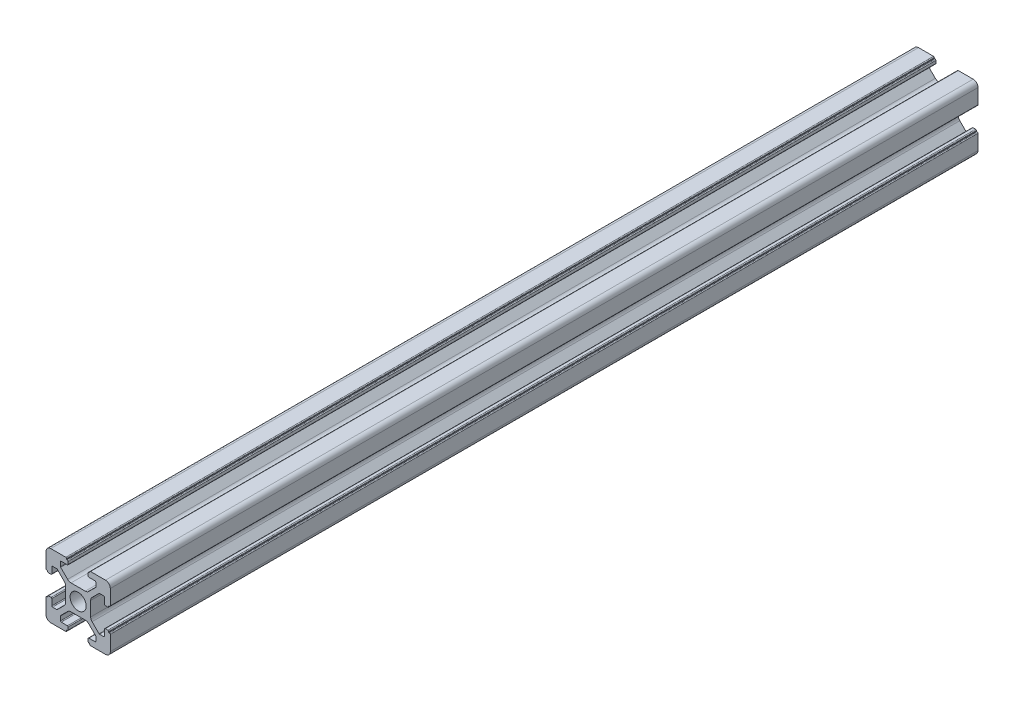
SolidWorks part; units mm, degrees
ref_plane "前视基准面" through (0, 0, 0) normal (0, 0, 1) x (1, 0, 0)
ref_plane "上视基准面" through (0, 0, 0) normal (0, 1, 0) x (1, 0, 0)
ref_plane "右视基准面" through (0, 0, 0) normal (1, 0, 0) x (0, 0, -1)
sketch "草图1" plane through (0, 0, 0) normal (0, 0, 1) x (1, 0, 0)
  line L0 (0, 0) -> (0, 5.5) construction
  line L1 (-8.5023, -10.0023) -> (-3.85, -10.0023)
  line L2 (-10.0023, -8.5023) -> (-10.0023, -3.85)
  line L3 (-8.5023, 10.0023) -> (-3.85, 10.0023)
  line L4 (10.0023, -8.5023) -> (10.0023, -3.85)
  line L5 (-10.0023, -10.0023) -> (10.0023, 10.0023) construction
  line L6 (-10.0023, 10.0023) -> (10.0023, -10.0023) construction
  line L7 (-2.218, -3.9) -> (2.218, -3.9)
  line L8 (-3.9, -2.218) -> (-3.9, 2.218)
  line L9 (-2.218, 3.9) -> (2.218, 3.9)
  line L10 (3.9, -2.218) -> (3.9, 2.218)
  line L11 (-3.9, -3.9) -> (3.9, 3.9) construction
  line L12 (-3.9, 3.9) -> (3.9, -3.9) construction
  line L13 (-5.25, -8.2) -> (-3.35, -8.2)
  line L14 (-8.2, -5.25) -> (-8.2, -3.35)
  line L15 (-5.25, 8.2) -> (-3.35, 8.2)
  line L16 (8.2, -5.25) -> (8.2, -3.35)
  line L17 (-8.2, -8.2) -> (8.2, 8.2) construction
  line L18 (-8.2, 8.2) -> (8.2, -8.2) construction
  line L19 (-7.95, 5.5) -> (-6.6642, 5.5)
  line L20 (0, 0) -> (5.5, 0) construction
  line L23 (-5.5, 7.95) -> (-5.5, 6.6642)
  line L26 (0, 0) -> (-0.5303, 0.5303)
  line L27 (3.2787, 4.3393) -> (5.4268, 6.4874)
  line L28 (0, 0) -> (0.5303, -0.5303)
  line L29 (5.5, 6.6642) -> (5.5, 7.95)
  line L30 (4.3393, 3.2787) -> (6.4874, 5.4268)
  line L31 (6.6642, 5.5) -> (7.95, 5.5)
  line L32 (4.3393, -3.2787) -> (6.4874, -5.4268)
  line L33 (3.2787, -4.3393) -> (5.4268, -6.4874)
  line L34 (-3.2787, -4.3393) -> (-5.4268, -6.4874)
  line L35 (-4.3393, -3.2787) -> (-6.4874, -5.4268)
  line L36 (-4.3393, 3.2787) -> (-6.4874, 5.4268)
  line L37 (-3.2787, 4.3393) -> (-5.4268, 6.4874)
  line L38 (3.1, -8.45) -> (3.1, -9.2523)
  line L39 (8.45, 3.1) -> (9.2523, 3.1)
  line L40 (-5.5, -6.6642) -> (-5.5, -7.95)
  line L41 (-6.6642, -5.5) -> (-7.95, -5.5)
  line L42 (5.5, -6.6642) -> (5.5, -7.95)
  line L43 (6.6642, -5.5) -> (7.95, -5.5)
  line L44 (9.2523, -3.1) -> (8.45, -3.1)
  line L46 (10.0023, 3.85) -> (10.0023, 8.5023)
  line L47 (8.2, 3.35) -> (8.2, 5.25)
  line L48 (-3.1, -9.2523) -> (-3.1, -8.45)
  line L49 (-8.45, -3.1) -> (-9.2523, -3.1)
  line L50 (-9.2523, 3.1) -> (-8.45, 3.1)
  line L51 (-3.1, 8.45) -> (-3.1, 9.2523)
  line L52 (3.1, 9.2523) -> (3.1, 8.45)
  line L53 (3.85, 10.0023) -> (8.5023, 10.0023)
  line L54 (3.35, 8.2) -> (5.25, 8.2)
  line L55 (-10.0023, 3.85) -> (-10.0023, 8.5023)
  line L56 (-8.2, 3.35) -> (-8.2, 5.25)
  line L57 (3.35, -8.2) -> (5.25, -8.2)
  line L58 (3.85, -10.0023) -> (8.5023, -10.0023)
  line L59 (9.7523, -3.6) -> (9.5023, -3.6)
  line L61 (9.7523, 3.6) -> (9.5023, 3.6)
  line L62 (9.5023, -3.6) -> (9.5023, -3.35)
  line L63 (3.6, -9.7523) -> (3.6, -9.5023)
  line L64 (3.35, -9.5023) -> (3.6, -9.5023)
  line L65 (9.5023, 3.35) -> (9.5023, 3.6)
  line L66 (-3.6, -9.5023) -> (-3.35, -9.5023)
  line L67 (-3.6, -9.7523) -> (-3.6, -9.5023)
  line L68 (-9.7523, -3.6) -> (-9.5023, -3.6)
  line L69 (-9.5023, -3.35) -> (-9.5023, -3.6)
  line L70 (-9.5023, 3.6) -> (-9.5023, 3.35)
  line L71 (-9.7523, 3.6) -> (-9.5023, 3.6)
  line L72 (-3.6, 9.7523) -> (-3.6, 9.5023)
  line L73 (-3.35, 9.5023) -> (-3.6, 9.5023)
  line L74 (3.6, 9.5023) -> (3.35, 9.5023)
  line L75 (3.6, 9.7523) -> (3.6, 9.5023)
  circle A0 centre (0, 0) radius 2.5
  arc A1 (10.0023, 8.5023) -> (8.5023, 10.0023) centre (8.5023, 8.5023) ccw
  arc A2 (8.5023, -10.0023) -> (10.0023, -8.5023) centre (8.5023, -8.5023) ccw
  arc A3 (-10.0023, -8.5023) -> (-8.5023, -10.0023) centre (-8.5023, -8.5023) ccw
  arc A4 (-10.0023, 8.5023) -> (-8.5023, 10.0023) centre (-8.5023, 8.5023) cw
  arc A5 (-9.5023, -3.35) -> (-9.2523, -3.1) centre (-9.2523, -3.35) cw
  arc A6 (-9.7523, -3.6) -> (-10.0023, -3.85) centre (-9.7523, -3.85) ccw
  arc A7 (-8.45, -3.1) -> (-8.2, -3.35) centre (-8.45, -3.35) cw
  arc A8 (-7.95, -5.5) -> (-8.2, -5.25) centre (-7.95, -5.25) cw
  arc A9 (-6.4874, -5.4268) -> (-6.6642, -5.5) centre (-6.6642, -5.25) cw
  arc A10 (-5.4268, -6.4874) -> (-5.5, -6.6642) centre (-5.25, -6.6642) ccw
  arc A11 (-5.5, -7.95) -> (-5.25, -8.2) centre (-5.25, -7.95) ccw
  arc A12 (-3.6, -9.7523) -> (-3.85, -10.0023) centre (-3.85, -9.7523) cw
  arc A13 (-3.35, -9.5023) -> (-3.1, -9.2523) centre (-3.35, -9.2523) ccw
  arc A14 (-3.1, -8.45) -> (-3.35, -8.2) centre (-3.35, -8.45) ccw
  arc A15 (3.1, -8.45) -> (3.35, -8.2) centre (3.35, -8.45) cw
  arc A16 (5.5, -7.95) -> (5.25, -8.2) centre (5.25, -7.95) cw
  arc A17 (5.4268, -6.4874) -> (5.5, -6.6642) centre (5.25, -6.6642) cw
  arc A18 (6.4874, -5.4268) -> (6.6642, -5.5) centre (6.6642, -5.25) ccw
  arc A19 (7.95, -5.5) -> (8.2, -5.25) centre (7.95, -5.25) ccw
  arc A20 (8.45, -3.1) -> (8.2, -3.35) centre (8.45, -3.35) ccw
  arc A21 (9.5023, -3.35) -> (9.2523, -3.1) centre (9.2523, -3.35) ccw
  arc A22 (9.7523, -3.6) -> (10.0023, -3.85) centre (9.7523, -3.85) cw
  arc A23 (3.35, -9.5023) -> (3.1, -9.2523) centre (3.35, -9.2523) cw
  arc A24 (3.6, -9.7523) -> (3.85, -10.0023) centre (3.85, -9.7523) ccw
  arc A25 (7.95, 5.5) -> (8.2, 5.25) centre (7.95, 5.25) cw
  arc A26 (8.2, 3.35) -> (8.45, 3.1) centre (8.45, 3.35) ccw
  arc A27 (9.5023, 3.35) -> (9.2523, 3.1) centre (9.2523, 3.35) cw
  arc A28 (9.7523, 3.6) -> (10.0023, 3.85) centre (9.7523, 3.85) ccw
  arc A29 (6.6642, 5.5) -> (6.4874, 5.4268) centre (6.6642, 5.25) ccw
  arc A30 (5.4268, 6.4874) -> (5.5, 6.6642) centre (5.25, 6.6642) ccw
  arc A31 (5.5, 7.95) -> (5.25, 8.2) centre (5.25, 7.95) ccw
  arc A32 (3.1, 8.45) -> (3.35, 8.2) centre (3.35, 8.45) ccw
  arc A33 (3.6, 9.7523) -> (3.85, 10.0023) centre (3.85, 9.7523) cw
  arc A34 (3.35, 9.5023) -> (3.1, 9.2523) centre (3.35, 9.2523) ccw
  arc A35 (-9.7523, 3.6) -> (-10.0023, 3.85) centre (-9.7523, 3.85) cw
  arc A36 (-9.5023, 3.35) -> (-9.2523, 3.1) centre (-9.2523, 3.35) ccw
  arc A37 (-8.45, 3.1) -> (-8.2, 3.35) centre (-8.45, 3.35) ccw
  arc A38 (-8.2, 5.25) -> (-7.95, 5.5) centre (-7.95, 5.25) cw
  arc A39 (-6.4874, 5.4268) -> (-6.6642, 5.5) centre (-6.6642, 5.25) ccw
  arc A40 (-5.4268, 6.4874) -> (-5.5, 6.6642) centre (-5.25, 6.6642) cw
  arc A41 (-5.5, 7.95) -> (-5.25, 8.2) centre (-5.25, 7.95) cw
  arc A42 (-3.1, 8.45) -> (-3.35, 8.2) centre (-3.35, 8.45) cw
  arc A43 (-3.1, 9.2523) -> (-3.35, 9.5023) centre (-3.35, 9.2523) ccw
  arc A44 (-3.6, 9.7523) -> (-3.85, 10.0023) centre (-3.85, 9.7523) ccw
  arc A45 (-4.3393, 3.2787) -> (-3.9, 2.218) centre (-5.4, 2.218) cw
  arc A46 (-3.2787, 4.3393) -> (-2.218, 3.9) centre (-2.218, 5.4) ccw
  arc A47 (3.2787, 4.3393) -> (2.218, 3.9) centre (2.218, 5.4) cw
  arc A48 (4.3393, 3.2787) -> (3.9, 2.218) centre (5.4, 2.218) ccw
  arc A49 (4.3393, -3.2787) -> (3.9, -2.218) centre (5.4, -2.218) cw
  arc A50 (3.2787, -4.3393) -> (2.218, -3.9) centre (2.218, -5.4) ccw
  arc A51 (-4.3393, -3.2787) -> (-3.9, -2.218) centre (-5.4, -2.218) ccw
  arc A52 (-2.218, -3.9) -> (-3.2787, -4.3393) centre (-2.218, -5.4) ccw
  point P0 (0, 0)
  point P7 (10.0023, 0)
  point P62 (0, 0)
  point P76 (0, 0)
  point P92 (-8.2, -5.5)
  point P99 (0, 0)
  point P106 (-5.5, -8.2)
  point P117 (5.5, -8.2)
  point P124 (8.2, -5.5)
  point P137 (8.2, 5.5)
  point P140 (8.2, 3.1)
  point P147 (6.5607, 5.5)
  point P152 (5.5, 8.2)
  point P167 (-8.2, 5.5)
  point P174 (-5.5, 8.2)
  dimension "D1" = 1.5
  dimension "D5" = 0.25
  dimension "D6" = 1.5
  dimension "D2" = 4
  dimension "D3" = 4
  dimension "D4" = 4
extrude "凸台-拉伸1" add sketch "草图1" along normal blind 270 contours A52 L7 A50 L33 A17 L42 A16 L57 A15 L38 A23 L64 L63 A24 L58 A2 L4 A22 L59 L62 A21 L44 A20 L16 A19 L43 A18 L32 A49 L10 A48 L30 A29 L31 A25 L47 A26 L39 A27 L65 L61 A28 L46 A1 L53 A33 L75 L74 A34 L52 A32
